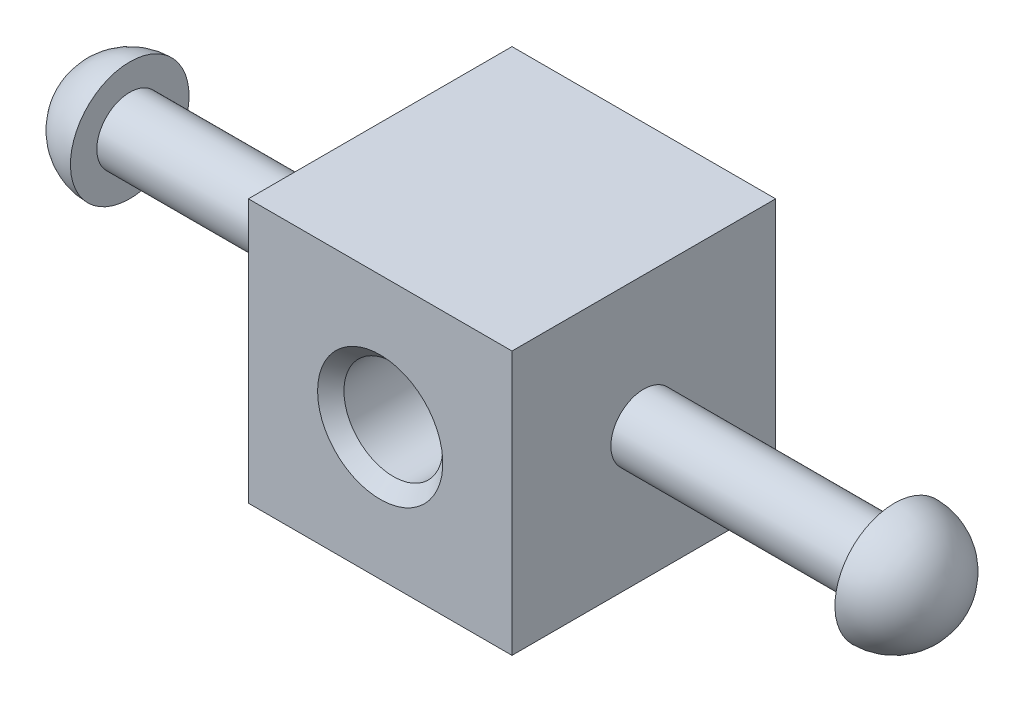
SolidWorks part; units mm, degrees
material "AISI 1020"
ref_plane "Front Plane" through (0, 0, 0) normal (0, 0, 1) x (1, 0, 0)
ref_plane "Top Plane" through (0, 0, 0) normal (0, 1, 0) x (1, 0, 0)
ref_plane "Right Plane" through (0, 0, 0) normal (1, 0, 0) x (0, 0, -1)
sketch "Sketch1" plane through (0, 0, 0) normal (0, 0, 1) x (1, 0, 0)
  line L1 (12.7, 12.7) -> (-12.7, 12.7)
  line L2 (12.7, 12.7) -> (12.7, -12.7)
  line L3 (12.7, -12.7) -> (-12.7, -12.7)
  line L4 (-12.7, 12.7) -> (-12.7, -12.7)
  line L5 (12.7, 12.7) -> (-12.7, -12.7) construction
  line L6 (12.7, -12.7) -> (-12.7, 12.7) construction
  circle A0 centre (0, 0) radius 4.7625
  point P0 (0, 0)
  dimension "D2" = 9.525
  dimension "D1" = 25.4
extrude "Boss-Extrude1" add sketch "Sketch1" along normal mid plane 25.4
chamfer "Chamfer1" distance 1.27 angle 45 2 edges at (4.7625, 0, -12.7) (4.7625, 0, 12.7)
sketch "Sketch2" plane through (0, 0, 0) normal (0, 0, 1) x (1, 0, 0)
  line L0 (0, 0) -> (0, 15.5318) construction
  line L1 (0, 0) -> (45.099, 0) construction
  line L2 (12.7, 3.175) -> (36.83, 3.175)
  line L3 (12.7, -12.7) -> (12.7, 12.7) construction
  line L4 (36.83, 3.175) -> (36.83, 5.715)
  line L5 (42.545, 0) -> (12.7, 0)
  line L6 (12.7, 3.175) -> (12.7, 0)
  arc A0 (36.83, 5.715) -> (42.545, 0) centre (36.83, 0) cw
  dimension "D2" = 5.715
  dimension "D1" = 6.35
  dimension "D3" = 73.66
revolve "Revolve1" add sketch "Sketch2" angle 360 about L5
mirror "Mirror1" about plane through (0, 0, 0) normal (1, 0, 0) of "Revolve1"
